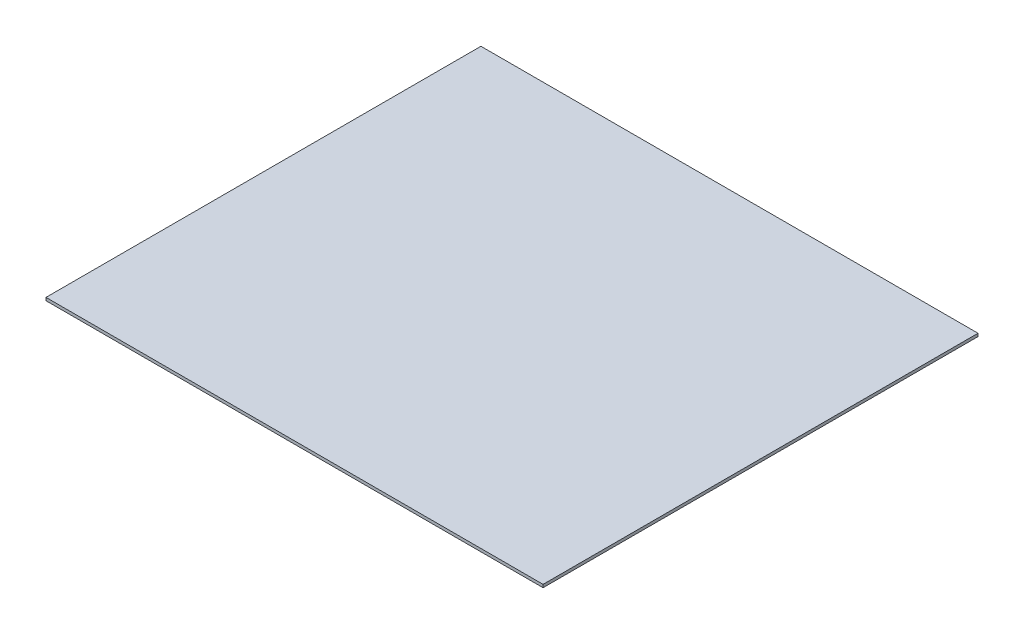
SolidWorks part; units mm, degrees
ref_plane "Front Plane" through (0, 0, 0) normal (0, 0, 1) x (1, 0, 0)
ref_plane "Top Plane" through (0, 0, 0) normal (0, 1, 0) x (1, 0, 0)
ref_plane "Right Plane" through (0, 0, 0) normal (1, 0, 0) x (0, 0, -1)
sketch "Sketch1" plane through (0, 0, 0) normal (0, 1, 0) x (1, 0, 0)
  line L1 (-406.4, 355.6) -> (406.4, 355.6)
  line L2 (-406.4, 355.6) -> (-406.4, -355.6)
  line L3 (-406.4, -355.6) -> (406.4, -355.6)
  line L4 (406.4, 355.6) -> (406.4, -355.6)
  line L5 (-406.4, 355.6) -> (406.4, -355.6) construction
  line L6 (-406.4, -355.6) -> (406.4, 355.6) construction
  point P0 (0, 0)
  dimension "D1" = 812.8
  dimension "D2" = 711.2
extrude "Boss-Extrude1" add sketch "Sketch1" along normal blind 4.8
